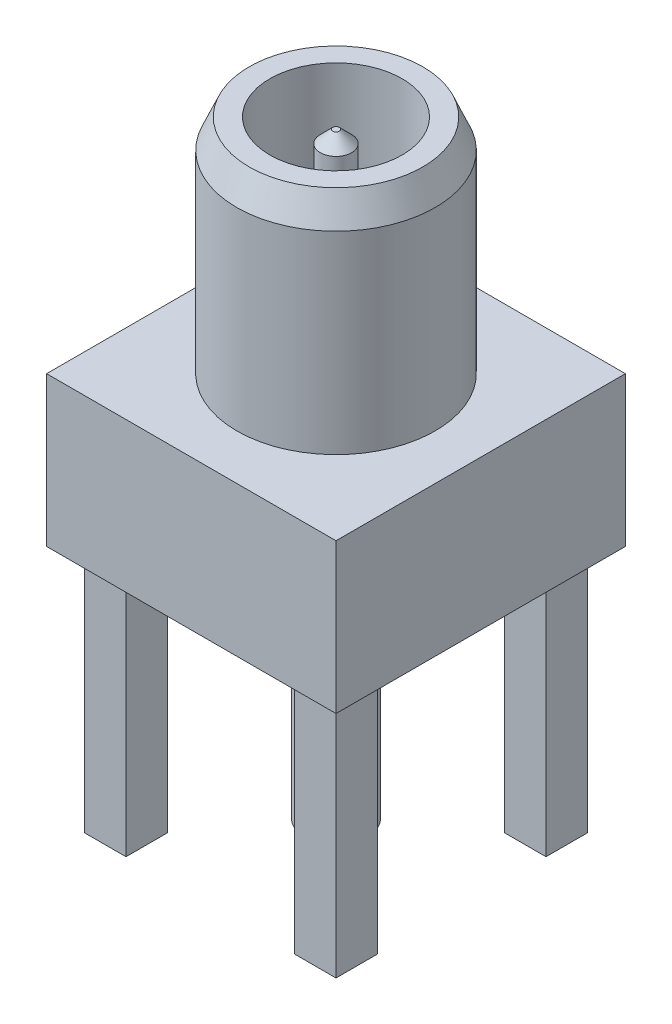
SolidWorks part; units mm, degrees
material "Pure Gold"
ref_plane "Front Plane" through (0, 0, 0) normal (0, 0, 1) x (1, 0, 0)
ref_plane "Top Plane" through (0, 0, 0) normal (0, 1, 0) x (1, 0, 0)
ref_plane "Right Plane" through (0, 0, 0) normal (1, 0, 0) x (0, 0, -1)
ref_plane "Plane4" through (0, 0, 0) normal (0, -1, 0) x (1, 0, 0)
sketch "Sketch1" plane through (0, 0, 0) normal (0, -1, 0) x (1, 0, 0)
  line L0 (-1.75, 1.75) -> (-1.75, -1.75)
  line L1 (-1.75, -1.75) -> (1.75, -1.75)
  line L2 (1.75, -1.75) -> (1.75, 1.75)
  line L3 (1.75, 1.75) -> (-1.75, 1.75)
  line L4 (-1.75, 1.75) -> (1.75, -1.75) construction
  point P4 (0, 0)
  dimension "D1" = 3.5
  dimension "D2" = 3.5
extrude "Boss-Extrude1" add sketch "Sketch1" against normal blind 1.81
sketch "Sketch2" plane through (0, 0, 0) normal (0, -1, 0) x (1, 0, 0)
  line L0 (-1.02, -1.52) -> (-1.52, -1.52)
  line L1 (-1.52, -1.52) -> (-1.52, -1.02)
  line L2 (-1.52, -1.02) -> (-1.02, -1.02)
  line L3 (-1.02, -1.02) -> (-1.02, -1.52)
  line L4 (-1.75, 1.75) -> (-1.75, -1.75) construction
  line L5 (-1.75, -1.75) -> (1.75, -1.75) construction
  line L6 (0, 1.75) -> (0, -1.75) construction
  line L7 (1.75, 1.75) -> (-1.75, 1.75) construction
  line L8 (1.75, 0) -> (-1.75, 0) construction
  line L9 (1.75, -1.75) -> (1.75, 1.75) construction
  line L10 (1.02, -1.02) -> (1.02, -1.52)
  line L11 (1.52, -1.02) -> (1.02, -1.02)
  line L12 (1.52, -1.52) -> (1.52, -1.02)
  line L13 (1.02, -1.52) -> (1.52, -1.52)
  line L14 (1.02, 1.52) -> (1.52, 1.52)
  line L15 (1.52, 1.52) -> (1.52, 1.02)
  line L16 (1.52, 1.02) -> (1.02, 1.02)
  line L17 (1.02, 1.02) -> (1.02, 1.52)
  line L18 (-1.02, 1.02) -> (-1.02, 1.52)
  line L19 (-1.52, 1.02) -> (-1.02, 1.02)
  line L20 (-1.52, 1.52) -> (-1.52, 1.02)
  line L21 (-1.02, 1.52) -> (-1.52, 1.52)
  dimension "D1" = 0.5
  dimension "D2" = 0.5
  dimension "D3" = 0.23
  dimension "D4" = 0.23
extrude "Boss-Extrude2" add sketch "Sketch2" along normal blind 3
sketch "Sketch3" plane through (0, 0, 0) normal (0, -1, 0) x (1, 0, 0)
  line L0 (-1.02, 1.02) -> (-1.52, 1.02)
  line L1 (-1.52, 1.02) -> (-1.52, 1.52)
  line L2 (-1.52, 1.52) -> (-1.02, 1.52)
  line L3 (-1.02, 1.52) -> (-1.02, 1.02)
extrude "Boss-Extrude3" [suppressed] add sketch "Sketch3" along normal blind 3
sketch "Sketch4" plane through (0, 0, 0) normal (0, -1, 0) x (1, 0, 0)
  line L0 (1.52, 1.02) -> (1.02, 1.02)
  line L1 (1.02, 1.02) -> (1.02, 1.52)
  line L2 (1.02, 1.52) -> (1.52, 1.52)
  line L3 (1.52, 1.52) -> (1.52, 1.02)
extrude "Boss-Extrude4" [suppressed] add sketch "Sketch4" along normal blind 3
sketch "Sketch5" plane through (0, 0, 0) normal (0, -1, 0) x (1, 0, 0)
  line L0 (1.52, -1.52) -> (1.02, -1.52)
  line L1 (1.02, -1.52) -> (1.02, -1.02)
  line L2 (1.02, -1.02) -> (1.52, -1.02)
  line L3 (1.52, -1.02) -> (1.52, -1.52)
extrude "Boss-Extrude5" [suppressed] add sketch "Sketch5" along normal blind 3
sketch "Sketch6" plane through (0, 0, 0) normal (0, -1, 0) x (1, 0, 0)
  circle A0 centre (0, 0) radius 1
  dimension "D1" = 2
extrude "Cut-Extrude1" cut sketch "Sketch6" against normal blind 0.001
sketch "Sketch7" plane through (0, 1.81, 0) normal (0, 1, 0) x (-1, 0, 0)
  circle A0 centre (0, 0) radius 1.2
  dimension "D1" = 2.4
extrude "Boss-Extrude6" add sketch "Sketch7" along normal blind 2.69
hole_wizard "Hole1" positions "Sketch9" profile "Sketch8" legacy
sketch "Sketch9" plane through (0, 4.5, 0) normal (0, 1, 0) x (1, 0, 0)
  circle A0 centre (0, 0) radius 1.2 construction
  point P0 (0, 0)
sketch "Sketch8" plane through (0, 4.5, 0) normal (1, 0, 0) x (0, 0, 1)
  line L0 (0, 0) -> (0, 1.45)
  line L1 (0, 1.45) -> (0.8, 1.45)
  line L2 (0.8, 1.45) -> (0.8, 0)
  line L3 (0.8, 0) -> (0, 0)
  line L4 (0, 110) -> (0, -10) construction
  dimension "Diameter" = 1.6
  dimension "Depth" = 1.45
ref_plane "Plane5" through (0, 0, 0) normal (0, 0, -1) x (-1, 0, 0)
ref_plane "Plane6" through (0, 0, 0) normal (0, 0, 1) x (1, 0, 0)
sketch "Sketch10" plane through (0, 0, 0) normal (0, 0, -1) x (-1, 0, 0)
  line L0 (-0.19, 3.05) -> (0, 3.05)
  line L1 (0, 3.05) -> (0, 4.37)
  line L2 (0, 4.37) -> (-0.0405, 4.37)
  line L3 (-0.0405, 4.37) -> (-0.19, 4.22) construction
  line L4 (-0.19, 4.22) -> (-0.19, 3.05)
  line L5 (0, 3.05) -> (0, 4.37) construction
  line L6 (-0.19, 4.22) -> (-0.19, 4.37)
  line L7 (-0.19, 4.37) -> (-0.0405, 4.37)
  line L8 (0.8, 3.05) -> (-0.8, 3.05) construction
  line L9 (0.8, 3.05) -> (-0.8, 3.05) construction
  dimension "D1" = 1.32
  dimension "D2" = 0.19
revolve "Revolve1" add sketch "Sketch10" angle 360 about L5
chamfer "Chamfer3" distance 0.15 angle 45 1 edges at (-0.19, 4.37, 0)
sketch "Sketch11" plane through (0, 0, 0) normal (0, 0, -1) x (-1, 0, 0)
  line L0 (-0.381, -3.001) -> (0, -3.001)
  line L1 (0, -3.001) -> (0, 0)
  line L2 (0, 0) -> (-0.381, 0)
  line L3 (-0.381, 0) -> (-0.381, -3.001)
  line L4 (0, -3.001) -> (0, 0) construction
  dimension "D1" = 3.001
  dimension "D2" = 0.381
revolve "Revolve2" [suppressed] add sketch "Sketch11" angle 360 about L4
sketch "Sketch12" plane through (0, 0.001, 0) normal (0, -1, 0) x (1, 0, 0)
  circle A0 centre (0, 0) radius 0.381
  dimension "D1" = 0.762
extrude "Boss-Extrude7" add sketch "Sketch12" along normal blind 3.001
chamfer "Chamfer1" distance 0.15 angle 45 1 edges at (0, -3, -0.381)
chamfer "Chamfer2" distance 0.35 distance2 0.15 1 edges at (0, 4.5, 1.2)
